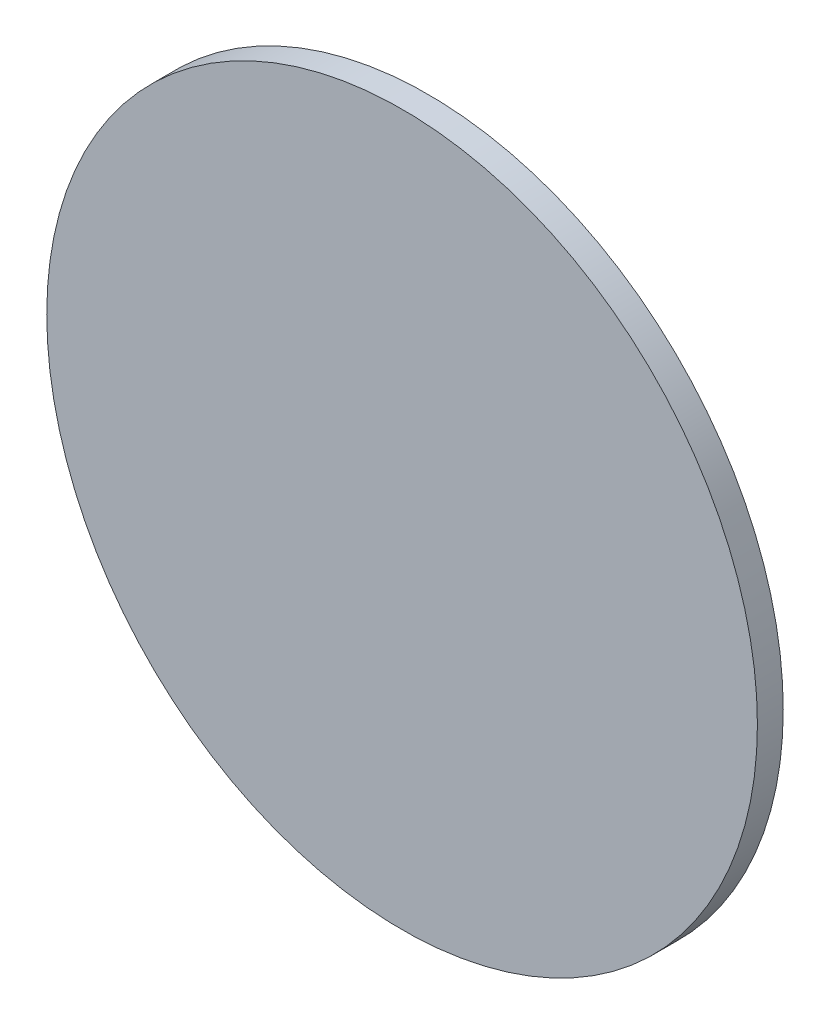
SolidWorks part; units mm, degrees
material "6061-T6 (SS)"
ref_plane "Front Plane" through (0, 0, 0) normal (0, 0, 1) x (1, 0, 0)
ref_plane "Top Plane" through (0, 0, 0) normal (0, 1, 0) x (1, 0, 0)
ref_plane "Right Plane" through (0, 0, 0) normal (1, 0, 0) x (0, 0, -1)
sketch "Sketch1" plane through (0, 0, 0) normal (0, 0, 1) x (1, 0, 0)
  circle A0 centre (0, 0) radius 82.55
  dimension "D1" = 165.1
extrude "Boss-Extrude1" add sketch "Sketch1" along normal blind 6
